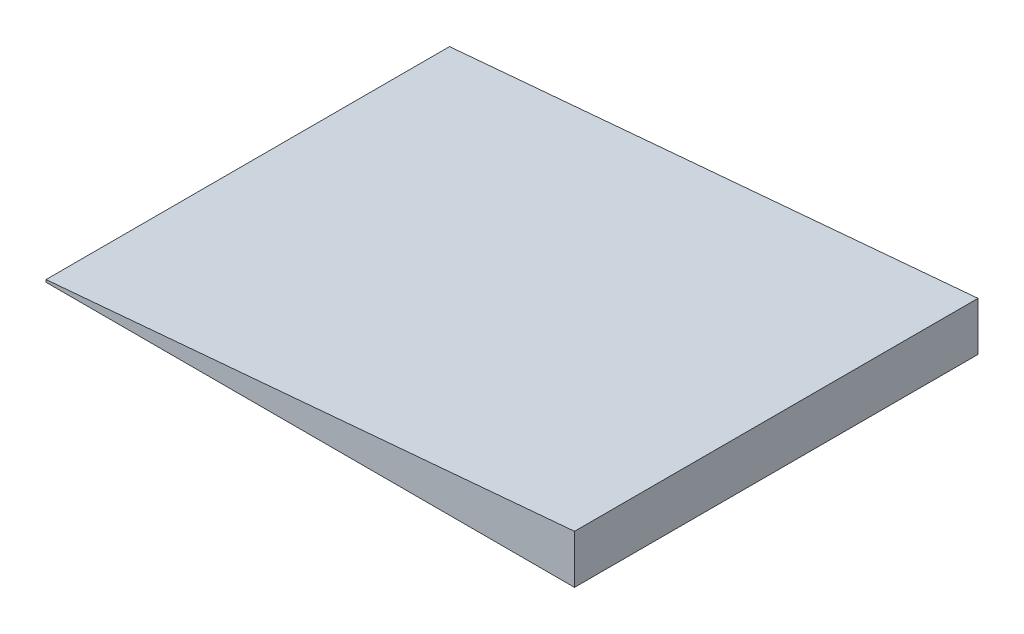
SolidWorks part; units mm, degrees
ref_plane "Front Plane" through (0, 0, 0) normal (0, 0, 1) x (1, 0, 0)
ref_plane "Top Plane" through (0, 0, 0) normal (0, 1, 0) x (1, 0, 0)
ref_plane "Right Plane" through (0, 0, 0) normal (1, 0, 0) x (0, 0, -1)
sketch "Sketch1" plane through (0, 0, 0) normal (0, 1, 0) x (1, 0, 0)
  line L1 (81.5694, -62.2772) -> (-81.5694, -62.2772)
  line L2 (81.5694, -62.2772) -> (81.5694, 62.2772)
  line L3 (81.5694, 62.2772) -> (-81.5694, 62.2772)
  line L4 (-81.5694, -62.2772) -> (-81.5694, 62.2772)
  line L5 (81.5694, -62.2772) -> (-81.5694, 62.2772) construction
  line L6 (81.5694, 62.2772) -> (-81.5694, -62.2772) construction
  point P0 (0, 0)
extrude "Boss-Extrude1" add sketch "Sketch1" along normal blind 15
ref_plane "Plane1" through (-0.6828, 7.8039, 0) normal (-0.0872, 0.9962, 0) x (0, 0, -1)
sketch "Sketch4" plane through (-0.6828, 7.8039, 0) normal (-0.0872, 0.9962, 0) x (0, 0, -1)
  line L1 (71.8376, -94.7024) -> (-71.8376, -94.7024)
  line L2 (71.8376, -94.7024) -> (71.8376, 94.7024)
  line L3 (71.8376, 94.7024) -> (-71.8376, 94.7024)
  line L4 (-71.8376, -94.7024) -> (-71.8376, 94.7024)
  line L5 (71.8376, -94.7024) -> (-71.8376, 94.7024) construction
  line L6 (71.8376, 94.7024) -> (-71.8376, -94.7024) construction
  point P0 (0, 0)
extrude "Cut-Extrude1" cut sketch "Sketch4" along normal blind 75
